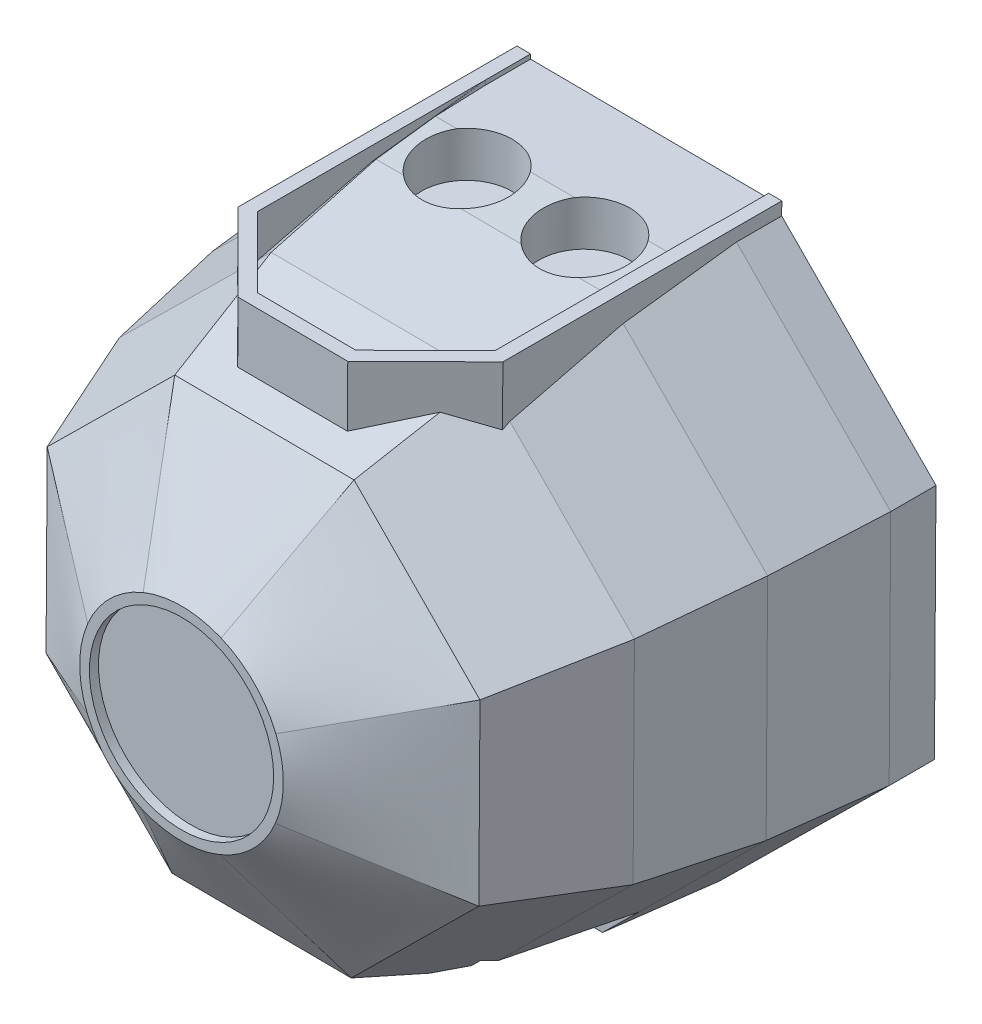
SolidWorks part; units mm, degrees
ref_plane "Frontal" through (0, 0, 0) normal (0, 0, 1) x (1, 0, 0)
ref_plane "Superior" through (0, 0, 0) normal (0, 1, 0) x (1, 0, 0)
ref_plane "Direito" through (0, 0, 0) normal (1, 0, 0) x (0, 0, -1)
sketch "Esboço1" plane through (0, 0, 0) normal (0, 0, 1) x (1, 0, 0)
  line L16 (11.7143, 142.5883) -> (-25.2409, 180.0263)
  line L17 (-25.2409, 180.0263) -> (-77.845, 180.3678)
  line L18 (-77.845, 180.3678) -> (-115.283, 143.4125)
  line L19 (-115.283, 143.4125) -> (-115.6245, 90.8085)
  line L20 (-115.6245, 90.8085) -> (-78.6693, 53.3704)
  line L21 (-78.6693, 53.3704) -> (-26.0652, 53.029)
  line L22 (-26.0652, 53.029) -> (11.3728, 89.9842)
  line L23 (11.3728, 89.9842) -> (11.7143, 142.5883)
extrude "Ressalto-extrusão1" add sketch "Esboço1" along normal blind 10
sketch "Esboço3" plane through (0, 0, 10) normal (0, 0, 1) x (1, 0, 0)
  line L8 (11.3728, 89.9842) -> (11.7143, 142.5883)
  line L9 (11.7143, 142.5883) -> (-25.2409, 180.0263)
  line L10 (-25.2409, 180.0263) -> (-77.845, 180.3678)
  line L11 (-77.845, 180.3678) -> (-115.283, 143.4125)
  line L12 (-115.283, 143.4125) -> (-115.6245, 90.8085)
  line L13 (-115.6245, 90.8085) -> (-78.6693, 53.3704)
  line L14 (-78.6693, 53.3704) -> (-26.0652, 53.029)
  line L15 (-26.0652, 53.029) -> (11.3728, 89.9842)
  line L16 (11.3728, 89.9842) -> (11.7143, 142.5883)
  line L17 (11.7143, 142.5883) -> (-25.2409, 180.0263)
  line L18 (-25.2409, 180.0263) -> (-77.845, 180.3678)
  line L19 (-77.845, 180.3678) -> (-115.283, 143.4125)
  line L20 (-115.283, 143.4125) -> (-115.6245, 90.8085)
  line L21 (-115.6245, 90.8085) -> (-78.6693, 53.3704)
  line L22 (-78.6693, 53.3704) -> (-26.0652, 53.029)
  line L23 (-26.0652, 53.029) -> (11.3728, 89.9842)
  dimension "D1" = 0
extrude "Ressalto-extrusão2" add sketch "Esboço3" along normal blind 25 draft 5
sketch "Esboço4" plane through (0, 0, 35) normal (0, 0, 1) x (1, 0, 0)
  line L8 (-26.957, 55.2221) -> (9.1916, 90.9044)
  line L9 (9.1916, 90.9044) -> (9.5212, 141.6965)
  line L10 (9.5212, 141.6965) -> (-26.1611, 177.845)
  line L11 (-26.1611, 177.845) -> (-76.9532, 178.1747)
  line L12 (-76.9532, 178.1747) -> (-113.1018, 142.4924)
  line L13 (-113.1018, 142.4924) -> (-113.4314, 91.7003)
  line L14 (-113.4314, 91.7003) -> (-77.7491, 55.5517)
  line L15 (-77.7491, 55.5517) -> (-26.957, 55.2221)
  line L16 (-26.957, 55.2221) -> (9.1916, 90.9044)
  line L17 (9.1916, 90.9044) -> (9.5212, 141.6965)
  line L18 (9.5212, 141.6965) -> (-26.1611, 177.845)
  line L19 (-26.1611, 177.845) -> (-76.9532, 178.1747)
  line L20 (-76.9532, 178.1747) -> (-113.1018, 142.4924)
  line L21 (-113.1018, 142.4924) -> (-113.4314, 91.7003)
  line L22 (-113.4314, 91.7003) -> (-77.7491, 55.5517)
  line L23 (-77.7491, 55.5517) -> (-26.957, 55.2221)
  dimension "D2" = 132.729
  dimension "D1" = 0
extrude "Ressalto-extrusão3" add sketch "Esboço4" along normal blind 25 draft 10
sketch "Esboço5" plane through (0, 0, 60) normal (0, 0, 1) x (1, 0, 0)
  line L8 (-75.8946, 59.948) -> (-28.7543, 59.642)
  line L9 (-28.7543, 59.642) -> (4.7953, 92.7589)
  line L10 (4.7953, 92.7589) -> (5.1013, 139.8992)
  line L11 (5.1013, 139.8992) -> (-28.0156, 173.4488)
  line L12 (-28.0156, 173.4488) -> (-75.1559, 173.7548)
  line L13 (-75.1559, 173.7548) -> (-108.7055, 140.6379)
  line L14 (-108.7055, 140.6379) -> (-109.0115, 93.4976)
  line L15 (-109.0115, 93.4976) -> (-75.8946, 59.948)
  line L16 (-75.8946, 59.948) -> (-28.7543, 59.642)
  line L17 (-28.7543, 59.642) -> (4.7953, 92.7589)
  line L18 (4.7953, 92.7589) -> (5.1013, 139.8992)
  line L19 (5.1013, 139.8992) -> (-28.0156, 173.4488)
  line L20 (-28.0156, 173.4488) -> (-75.1559, 173.7548)
  line L21 (-75.1559, 173.7548) -> (-108.7055, 140.6379)
  line L22 (-108.7055, 140.6379) -> (-109.0115, 93.4976)
  line L23 (-109.0115, 93.4976) -> (-75.8946, 59.948)
  dimension "D1" = 0
extrude "Ressalto-extrusão4" add sketch "Esboço5" along normal blind 25 draft 20
sketch "Esboço8" plane through (0, 0, 85) normal (0, 0, 1) x (1, 0, 0)
  circle A0 centre (-51.9551, 116.6984) radius 5
extrude "Ressalto-extrusão6" add sketch "Esboço8" along normal blind 18
sketch "Esboço7" plane through (0, 0, 103) normal (0, 0, 1) x (1, 0, 0)
  circle A0 centre (-51.9551, 116.6984) radius 22.5
  dimension "D1" = 45
sketch "Esboço6" plane through (0, 0, 85) normal (0, 0, 1) x (1, 0, 0)
  line L0 (-99.7594, 117.0087) -> (-4.1508, 116.3881) construction
  line L8 (-99.888, 97.2075) -> (-72.0666, 69.0226)
  line L9 (-72.0666, 69.0226) -> (-32.4642, 68.7655)
  line L10 (-32.4642, 68.7655) -> (-4.2793, 96.5869)
  line L11 (-4.2793, 96.5869) -> (-4.0222, 136.1893)
  line L12 (-4.0222, 136.1893) -> (-31.8436, 164.3742)
  line L13 (-31.8436, 164.3742) -> (-71.446, 164.6313)
  line L14 (-71.446, 164.6313) -> (-99.6309, 136.8099)
  line L15 (-99.6309, 136.8099) -> (-99.888, 97.2075)
  line L16 (-99.888, 97.2075) -> (-72.0666, 69.0226)
  line L17 (-72.0666, 69.0226) -> (-32.4642, 68.7655)
  line L18 (-32.4642, 68.7655) -> (-4.2793, 96.5869)
  line L19 (-4.2793, 96.5869) -> (-4.0222, 136.1893)
  line L20 (-4.0222, 136.1893) -> (-31.8436, 164.3742)
  line L21 (-31.8436, 164.3742) -> (-71.446, 164.6313)
  line L22 (-71.446, 164.6313) -> (-99.6309, 136.8099)
  line L23 (-99.6309, 136.8099) -> (-99.888, 97.2075)
  dimension "D1" = 0
loft "Loft1" add profiles "Esboço6", "Esboço7"
sketch "Esboço9" plane through (0, 0, 103) normal (0, 0, 1) x (1, 0, 0)
  arc A0 (-70.7127, 124.6111) -> (-70.8139, 109.0299) centre (-51.9551, 116.6984) ccw
  arc A1 (-70.8139, 109.0299) -> (-59.8678, 97.9407) centre (-51.9551, 116.6984) ccw
  arc A2 (-59.8678, 97.9407) -> (-44.2866, 97.8396) centre (-51.9551, 116.6984) ccw
  arc A3 (-44.2866, 97.8396) -> (-33.1974, 108.7857) centre (-51.9551, 116.6984) ccw
  arc A4 (-33.1974, 108.7857) -> (-33.0963, 124.3669) centre (-51.9551, 116.6984) ccw
  arc A5 (-33.0963, 124.3669) -> (-44.0424, 135.456) centre (-51.9551, 116.6984) ccw
  arc A6 (-44.0424, 135.456) -> (-59.6236, 135.5572) centre (-51.9551, 116.6984) ccw
  arc A7 (-59.6236, 135.5572) -> (-70.7127, 124.6111) centre (-51.9551, 116.6984) ccw
  arc A8 (-72.6861, 125.4435) -> (-72.7978, 108.2231) centre (-51.9551, 116.6984) ccw
  arc A9 (-72.7978, 108.2231) -> (-60.7002, 95.9674) centre (-51.9551, 116.6984) ccw
  arc A10 (-60.7002, 95.9674) -> (-43.4798, 95.8557) centre (-51.9551, 116.6984) ccw
  arc A11 (-43.4798, 95.8557) -> (-31.2241, 107.9533) centre (-51.9551, 116.6984) ccw
  arc A12 (-31.2241, 107.9533) -> (-31.1124, 125.1737) centre (-51.9551, 116.6984) ccw
  arc A13 (-31.1124, 125.1737) -> (-43.21, 137.4294) centre (-51.9551, 116.6984) ccw
  arc A14 (-43.21, 137.4294) -> (-60.4304, 137.5411) centre (-51.9551, 116.6984) ccw
  arc A15 (-60.4304, 137.5411) -> (-72.6861, 125.4435) centre (-51.9551, 116.6984) ccw
  arc A16 (-72.6861, 125.4435) -> (-72.7978, 108.2231) centre (-51.9551, 116.6984) ccw
  arc A17 (-72.7978, 108.2231) -> (-60.7002, 95.9674) centre (-51.9551, 116.6984) ccw
  arc A18 (-60.7002, 95.9674) -> (-43.4798, 95.8557) centre (-51.9551, 116.6984) ccw
  arc A19 (-43.4798, 95.8557) -> (-31.2241, 107.9533) centre (-51.9551, 116.6984) ccw
  arc A20 (-31.2241, 107.9533) -> (-31.1124, 125.1737) centre (-51.9551, 116.6984) ccw
  arc A21 (-31.1124, 125.1737) -> (-43.21, 137.4294) centre (-51.9551, 116.6984) ccw
  arc A22 (-43.21, 137.4294) -> (-60.4304, 137.5411) centre (-51.9551, 116.6984) ccw
  arc A23 (-60.4304, 137.5411) -> (-72.6861, 125.4435) centre (-51.9551, 116.6984) ccw
  dimension "D1" = 0
extrude "Corte-extrusão2" cut sketch "Esboço9" against normal blind 2 contours A6 A7 A0 A1 A2 A3 A4 A5
sketch "Esboço10" plane through (0, 0, 0) normal (0, 0, 1) x (1, 0, 0)
  line L0 (-77.845, 180.3678) -> (-77.8709, 176.3679)
  line L1 (-25.2409, 180.0263) -> (-25.2669, 176.0264)
  line L2 (-25.2409, 180.0263) -> (-77.845, 180.3678) construction
  line L3 (-25.2409, 180.0263) -> (-77.845, 180.3678)
  line L4 (-77.8709, 176.3679) -> (-25.2669, 176.0264)
sketch "Esboço12" plane through (1.1674, 179.8549, 0) normal (0.0065, 1, 0) x (1, -0.0065, 0)
  line L0 (-82.014, 0) -> (-82.014, -61.6157)
  line L1 (-82.014, -61.6157) -> (-64.8797, -78.75)
  line L2 (-64.8797, -78.75) -> (-40.6482, -78.75)
  line L3 (-40.6482, -78.75) -> (-23.514, -61.6157)
  line L4 (-23.514, -61.6157) -> (-23.514, 0)
  line L5 (-26.514, 0) -> (-23.514, 0)
  line L6 (-26.514, -60.3731) -> (-26.514, 0)
  line L7 (-26.514, 0) -> (-79.014, 0)
  line L8 (-79.014, 0) -> (-79.014, -60.3731)
  line L9 (-79.014, -60.3731) -> (-63.6371, -75.75)
  line L10 (-63.6371, -75.75) -> (-41.8909, -75.75)
  line L11 (-41.8909, -75.75) -> (-26.514, -60.3731)
  line L12 (-26.514, -60.3731) -> (-26.514, 0)
  line L13 (-26.514, 0) -> (-79.014, 0)
  line L14 (-79.014, 0) -> (-79.014, -60.3731)
  line L15 (-79.014, -60.3731) -> (-63.6371, -75.75)
  line L16 (-63.6371, -75.75) -> (-41.8909, -75.75)
  line L17 (-41.8909, -75.75) -> (-26.514, -60.3731)
  line L18 (-79.014, 0) -> (-82.014, 0)
  circle A0 centre (-39.764, -27.25) radius 8.3 construction
  circle A1 centre (-39.764, -27.25) radius 8.3
  circle A2 centre (-65.764, -27.25) radius 8.3 construction
  circle A3 centre (-65.764, -27.25) radius 8.3
  circle A4 centre (-52.764, -54.25) radius 4 construction
  circle A5 centre (-52.764, -54.25) radius 4
  line M8 (-79.014, 0) -> (-79.014, -10)
  line M9 (-79.014, -10) -> (-26.4089, -10)
  line M10 (-26.4089, -10) -> (-26.4089, 0)
  dimension "D1" = 0
extrude "Ressalto-extrusão10" add sketch "Esboço12" against normal blind 50 separate body contours L18 L0 L1 L2 L3 L4 L5 L12 L17 L16 L15 L14 M8 M10 M9
sketch "Esboço13" plane through (0, 0, 0) normal (0, 0, 1) x (1, 0, 0)
  line L4 (-77.7491, 55.5517) -> (-26.957, 55.2221)
  line L5 (-26.957, 55.2221) -> (-28.7543, 59.642)
  line L6 (-28.7543, 59.642) -> (-75.8946, 59.948)
  line L7 (-75.8946, 59.948) -> (-77.7491, 55.5517)
  line L8 (-98.0707, 55.6836) -> (-5.6515, 55.0838)
  line L9 (-5.6515, 55.0838) -> (-7.4254, 63.0955)
  line L10 (-7.4254, 63.0955) -> (-96.1929, 63.6716)
  line L11 (-96.1929, 63.6716) -> (-98.0707, 55.6836)
  dimension "D2" = 8
  dimension "D1" = 0
extrude "Corte-extrusão5" cut sketch "Esboço13" along normal blind 50 from offset 35
sketch "Esboço15" plane through (0.4092, 63.0446, 0) normal (-0.0065, -1, 0) x (1, -0.0065, 0)
  line L0 (-78.3114, 60.3) -> (-62.3114, 60.3) construction
  line L1 (-79.3114, 61.3) -> (-60.1114, 61.3)
  line L2 (-60.1114, 61.3) -> (-60.1114, 63.8)
  line L3 (-78.3114, 60.3) -> (-59.1114, 60.3) construction
  line L4 (-25.5114, 63.8) -> (-60.1114, 63.8)
  line L5 (-78.3114, 60.3) -> (-78.3114, 47) construction
  line L6 (-59.1114, 48.9) -> (-59.1114, 60.9) construction
  line L7 (-59.1114, 60.3) -> (-59.1114, 62.8) construction
  line L8 (-28.3114, 62.8) -> (-39.3114, 62.8) construction
  line L9 (-26.5114, 62.8) -> (-59.1114, 62.8) construction
  line L10 (-26.5114, 60.9) -> (-26.5114, 48.9) construction
  line L11 (-26.5114, 62.8) -> (-26.5114, 47) construction
  line L12 (-39.3114, 47) -> (-28.3114, 47) construction
  line L13 (-78.3114, 47) -> (-26.5114, 47) construction
  line L14 (-25.5114, 63.8) -> (-25.5114, 46)
  line L15 (-79.3114, 46) -> (-25.5114, 46)
  line L16 (-79.3114, 61.3) -> (-79.3114, 46)
extrude "Corte-extrusão6" cut sketch "Esboço15" against normal blind 20
sketch "Esboço16" plane through (1.1674, 179.8549, 0) normal (0.0065, 1, 0) x (1, -0.0065, 0)
  line L0 (-26.4089, 0) -> (-79.014, 0) construction
  line L1 (-79.014, 0) -> (-79.014, -10) construction
  line L2 (-26.4089, -10) -> (-26.4089, 0) construction
  line L3 (-79.014, -10) -> (-78.108, -35) construction
  line L4 (-78.108, -35) -> (-27.3148, -35) construction
  line L5 (-27.3148, -35) -> (-26.4089, -10) construction
  line L6 (-26.4089, 0) -> (-79.014, 0)
  line L7 (-79.014, 0) -> (-79.014, -10)
  line L8 (-26.4089, -10) -> (-26.4089, 0)
  line L9 (-79.014, -10) -> (-78.108, -35)
  line L10 (-78.108, -35) -> (-27.3148, -35)
  line L11 (-27.3148, -35) -> (-26.4089, -10)
extrude "Corte-extrusão7" cut sketch "Esboço16" against normal blind 1
sketch "Esboço17" plane through (1.1609, 178.855, 0) normal (0.0065, 1, 0) x (1, -0.0065, 0)
  circle A0 centre (-39.764, -27.25) radius 10
  circle A1 centre (-65.764, -27.25) radius 10
extrude "Corte-extrusão8" cut sketch "Esboço17" against normal blind 10
combine bodies "Combinar1" operation type add bodies to combine 119 117
